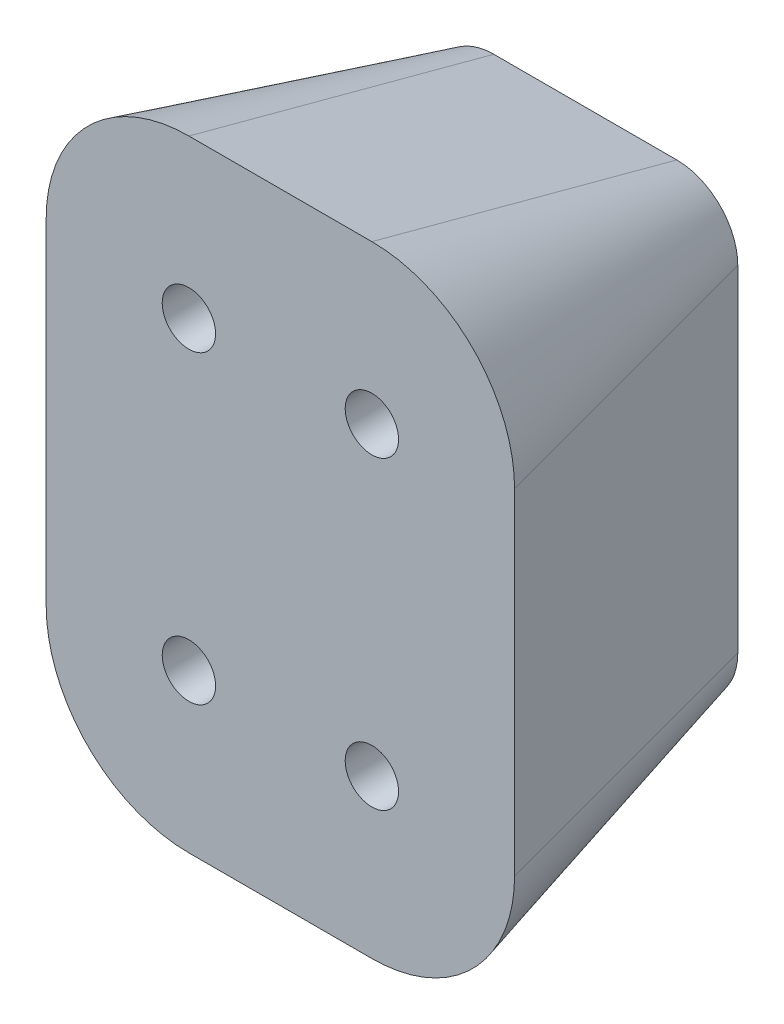
SolidWorks part; units mm, degrees
ref_plane "Front Plane" through (0, 0, 0) normal (0, 0, 1) x (1, 0, 0)
ref_plane "Top Plane" through (0, 0, 0) normal (0, 1, 0) x (1, 0, 0)
ref_plane "Right Plane" through (0, 0, 0) normal (1, 0, 0) x (0, 0, -1)
sketch "Sketch1" plane through (0, 0, 0) normal (0, 0, 1) x (1, 0, 0)
  line L0 (-20.5984, 10) -> (26.0825, 10) construction
  line L1 (-6, 15) -> (6, 15)
  line L2 (-10, 11) -> (-10, -11)
  line L3 (-6, -15) -> (6, -15)
  line L4 (10, 11) -> (10, -11)
  line L5 (-10, 15) -> (10, -15) construction
  line L6 (-10, -15) -> (10, 15) construction
  line L7 (-20.5984, -10) -> (26.0825, -10) construction
  line L8 (-6, 19.5876) -> (-6, -25.1546) construction
  line L9 (6, 19.5876) -> (6, -25.1546) construction
  circle A0 centre (-6, 10) radius 1.75
  circle A1 centre (6, 10) radius 1.75
  circle A2 centre (-6, -10) radius 1.75
  circle A3 centre (6, -10) radius 1.75
  arc A4 (6, -15) -> (10, -11) centre (6, -11) ccw
  arc A5 (-10, -11) -> (-6, -15) centre (-6, -11) ccw
  arc A6 (6, 15) -> (10, 11) centre (6, 11) cw
  arc A7 (-10, 11) -> (-6, 15) centre (-6, 11) cw
  point P0 (0, 0)
  dimension "D7" = 3.5
  dimension "D8" = 4
  dimension "D1" = 10
  dimension "D2" = 10
  dimension "D3" = 6
  dimension "D4" = 6
  dimension "D5" = 20
  dimension "D6" = 5
extrude "Boss-Extrude1" add sketch "Sketch1" along normal blind 5
sketch "Sketch4" plane through (0, 0, 5) normal (0, 0, 1) x (1, 0, 0)
  line L0 (-6, -15) -> (6, -15) construction
  line L1 (-10, 11) -> (-10, -11) construction
  line L2 (6, 15) -> (-6, 15) construction
  line L3 (10, -11) -> (10, 11) construction
  line L4 (-6, -15) -> (6, -15)
  line L5 (-10, 11) -> (-10, -11)
  line L6 (6, 15) -> (-6, 15)
  line L7 (10, -11) -> (10, 11)
  arc A0 (6, -15) -> (10, -11) centre (6, -11) ccw construction
  arc A1 (-10, -11) -> (-6, -15) centre (-6, -11) ccw construction
  arc A2 (-6, 15) -> (-10, 11) centre (-6, 11) ccw construction
  arc A3 (10, 11) -> (6, 15) centre (6, 11) ccw construction
  arc A4 (6, -15) -> (10, -11) centre (6, -11) ccw
  arc A5 (-10, -11) -> (-6, -15) centre (-6, -11) ccw
  arc A6 (-6, 15) -> (-10, 11) centre (-6, 11) ccw
  arc A7 (10, 11) -> (6, 15) centre (6, 11) ccw
extrude "Boss-Extrude2" add sketch "Sketch4" along normal blind 20 draft 15 draft outward yes
sketch "Sketch5" plane through (0, 0, 0) normal (0, 0, -1) x (-1, 0, 0)
  circle A0 centre (-6, -10) radius 1.75 construction
  circle A1 centre (6, -10) radius 1.75 construction
  circle A2 centre (6, 10) radius 1.75 construction
  circle A3 centre (-6, 10) radius 1.75 construction
  circle A4 centre (-6, -10) radius 1.75
  circle A5 centre (6, -10) radius 1.75
  circle A6 centre (6, 10) radius 1.75
  circle A7 centre (-6, 10) radius 1.75
extrude "Cut-Extrude1" cut sketch "Sketch5" against normal up to next
sketch "Sketch6" plane through (0, 0, 0) normal (0, 0, -1) x (-1, 0, 0)
  line L0 (6, -15) -> (-6, -15) construction
  line L1 (-10, -11) -> (-10, 11) construction
  line L2 (-6, 15) -> (6, 15) construction
  line L3 (10, 11) -> (10, -11) construction
  line L4 (6, -15) -> (-6, -15)
  line L5 (-10, -11) -> (-10, 11)
  line L6 (-6, 15) -> (6, 15)
  line L7 (10, 11) -> (10, -11)
  arc A0 (6, -15) -> (10, -11) centre (6, -11) ccw construction
  arc A1 (-10, -11) -> (-6, -15) centre (-6, -11) ccw construction
  arc A2 (-6, 15) -> (-10, 11) centre (-6, 11) ccw construction
  arc A3 (10, 11) -> (6, 15) centre (6, 11) ccw construction
  arc A4 (6, -15) -> (10, -11) centre (6, -11) ccw
  arc A5 (-10, -11) -> (-6, -15) centre (-6, -11) ccw
  arc A6 (-6, 15) -> (-10, 11) centre (-6, 11) ccw
  arc A7 (10, 11) -> (6, 15) centre (6, 11) ccw
extrude "Cut-Extrude2" cut sketch "Sketch6" against normal blind 5
